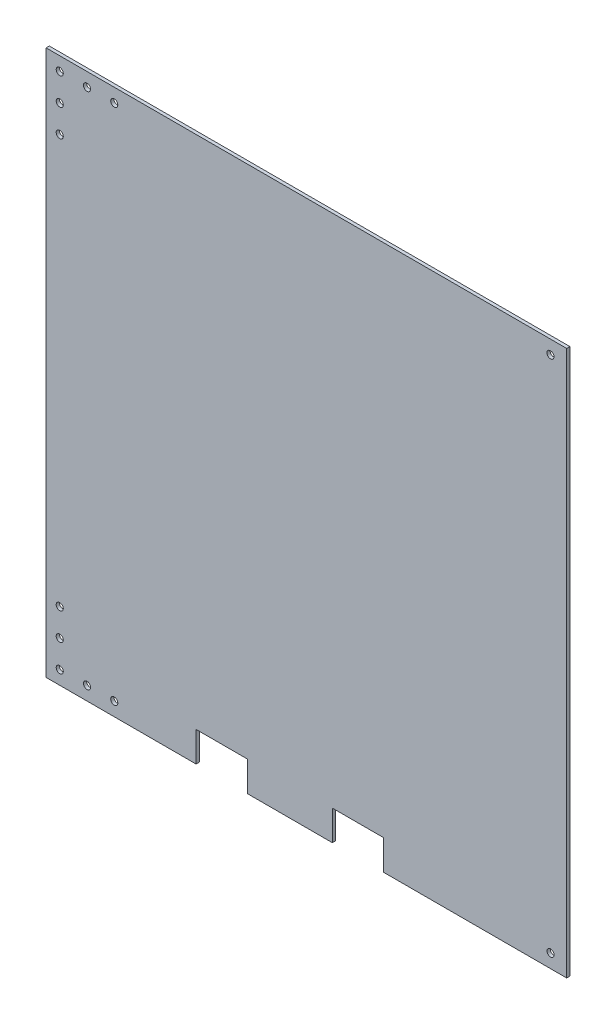
SolidWorks part; units mm, degrees
ref_plane "Front Plane" through (0, 0, 0) normal (0, 0, 1) x (1, 0, 0)
ref_plane "Top Plane" through (0, 0, 0) normal (0, 1, 0) x (1, 0, 0)
ref_plane "Right Plane" through (0, 0, 0) normal (1, 0, 0) x (0, 0, -1)
sketch "Sketch1" plane through (0, 0, 0) normal (0, 0, 1) x (1, 0, 0)
  line L1 (1073.9532, -36.1013) -> (1558.9532, -36.1013)
  line L2 (1073.9532, -36.1013) -> (1073.9532, -544.1013)
  line L3 (1073.9532, -544.1013) -> (1558.9532, -544.1013)
  line L4 (1558.9532, -36.1013) -> (1558.9532, -544.1013)
  dimension "D1" = 508
  dimension "D2" = 485
extrude "Boss-Extrude1" add sketch "Sketch1" along normal blind 3
sketch "Sketch2" plane through (0, 0, 3) normal (0, 0, 1) x (1, 0, 0)
  line L0 (1558.9532, -36.1013) -> (1073.9532, -36.1013) construction
  line L1 (1073.9532, -36.1013) -> (1073.9532, -544.1013) construction
  line L2 (1558.9532, -544.1013) -> (1558.9532, -36.1013) construction
  line L3 (1073.9532, -544.1013) -> (1558.9532, -544.1013) construction
  circle A0 centre (1086.6532, -48.8013) radius 3.295
  circle A1 centre (1543.8532, -48.8013) radius 3.295
  circle A2 centre (1543.9672, -531.4013) radius 3.295
  circle A3 centre (1086.6532, -531.4013) radius 3.295
  dimension "D1" = 6.59
  dimension "D2" = 12.7
  dimension "D3" = 12.7
  dimension "D4" = 6.59
  dimension "D5" = 12.7
  dimension "D6" = 15.1
  dimension "D7" = 6.59
  dimension "D8" = 12.7
  dimension "D9" = 14.986
  dimension "D10" = 6.59
  dimension "D11" = 12.7
  dimension "D12" = 12.7
extrude "Cut-Extrude1" cut sketch "Sketch2" against normal blind 3
sketch "Sketch3" plane through (0, 0, 3) normal (0, 0, 1) x (1, 0, 0)
  line L0 (1073.9532, -544.1013) -> (1558.9532, -544.1013) construction
  line L12 (1073.9532, -36.1013) -> (1073.9532, -544.1013) construction
  line L13 (1213.6532, -544.1013) -> (1261.4052, -544.1013)
  line L14 (1213.6532, -544.1013) -> (1213.6532, -516.1613)
  line L15 (1213.6532, -516.1613) -> (1261.4052, -516.1613)
  line L16 (1261.4052, -544.1013) -> (1261.4052, -516.1613)
  line L19 (1340.6532, -544.1013) -> (1388.4052, -544.1013)
  line L20 (1340.6532, -544.1013) -> (1340.6532, -516.1613)
  line L21 (1340.6532, -516.1613) -> (1388.4052, -516.1613)
  line L22 (1388.4052, -544.1013) -> (1388.4052, -516.1613)
  dimension "D1" = 139.7
  dimension "D2" = 27.94
  dimension "D3" = 47.752
  dimension "D4" = 266.7
  dimension "D5" = 27.94
  dimension "D6" = 47.752
extrude "Cut-Extrude2" cut sketch "Sketch3" against normal through all
sketch "Sketch4" plane through (0, 0, 3) normal (0, 0, 1) x (1, 0, 0)
  circle A0 centre (1112.0532, -48.8013) radius 3.302
  circle A1 centre (1137.4532, -48.8013) radius 3.302
  circle A2 centre (1086.6532, -74.2013) radius 3.302
  circle A3 centre (1086.6532, -99.6013) radius 3.302
  circle A4 centre (1086.6532, -480.6013) radius 3.302
  circle A5 centre (1086.6532, -506.0013) radius 3.302
  circle A6 centre (1112.0532, -531.4013) radius 3.302
  circle A7 centre (1137.4532, -531.4013) radius 3.302
  dimension "D1" = 6.604
  dimension "D2" = 6.604
  dimension "D3" = 6.604
  dimension "D4" = 6.604
  dimension "D5" = 6.604
  dimension "D6" = 6.604
  dimension "D7" = 6.604
  dimension "D8" = 6.604
extrude "Cut-Extrude3" cut sketch "Sketch4" against normal through all
